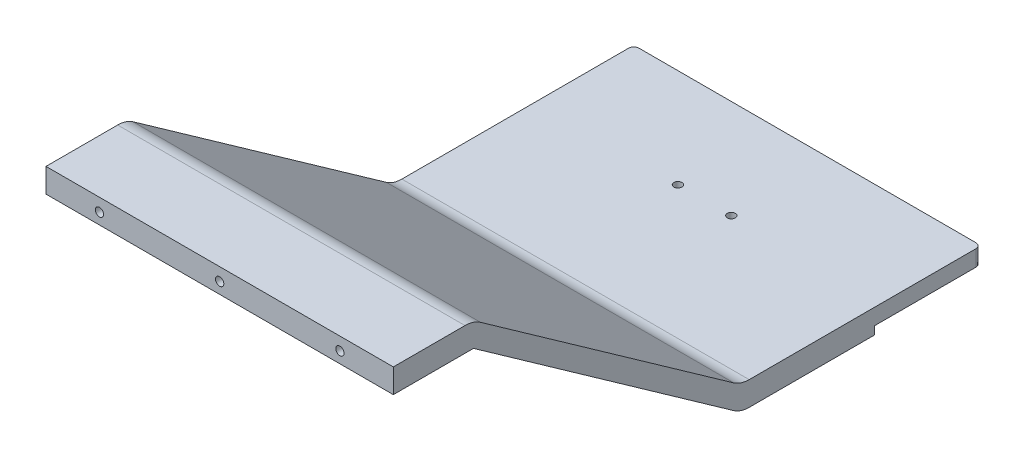
SolidWorks part; units mm, degrees
ref_plane "前视基准面" through (0, 0, 0) normal (0, 0, 1) x (1, 0, 0)
ref_plane "上视基准面" through (0, 0, 0) normal (0, 1, 0) x (1, 0, 0)
ref_plane "右视基准面" through (0, 0, 0) normal (1, 0, 0) x (0, 0, -1)
other "Configuration Table"
sketch "草图1" plane through (0, 0, 0) normal (0, 0, 1) x (1, 0, 0)
  line L0 (0, 0) -> (0, 79)
  line L1 (0, 79) -> (79, 79)
  line L2 (79, 79) -> (79, 70)
  line L3 (79, 70) -> (9, 70)
  line L4 (9, 70) -> (9, 0)
  line L5 (9, 0) -> (0, 0)
  dimension "D1" = 9
  dimension "D2" = 9
  dimension "D3" = 70
  dimension "D4" = 70
ref_plane "基准面1" through (0, 0, 100) normal (0, 0, 1) x (1, 0, 0)
sketch "草图2" plane through (0, 0, 100) normal (0, 0, 1) x (1, 0, 0)
  line L0 (0, 79) -> (-70.7107, 149.7107) construction
  line L1 (0, 0) -> (0, 79) construction
  line L2 (-70.7107, 149.7107) -> (-70.7107, 0)
  line L3 (-70.7107, 0) -> (-61.7107, 0)
  line L4 (-61.7107, 0) -> (-61.7107, 140.7107)
  line L5 (-61.7107, 140.7107) -> (79, 140.7107)
  line L6 (79, 140.7107) -> (79, 149.7107)
  line L7 (79, 149.7107) -> (-70.7107, 149.7107)
  line L8 (0, 0) -> (0, 79) construction
  line L9 (0, 79) -> (79, 79) construction
  dimension "D1" = 135
  dimension "D2" = 9
  dimension "D3" = 100
  dimension "D4" = 79
loft "放样1" add profiles "草图1", "草图2"
sketch "草图4" plane through (0, 0, 0) normal (0, 0, -1) x (-1, 0, 0)
  line L7 (-9, 0) -> (0, 0)
  line L8 (0, 0) -> (0, 79)
  line L9 (0, 79) -> (-79, 79)
  line L10 (-79, 79) -> (-79, 70)
  line L11 (-79, 70) -> (-77.7656, 70)
  line L12 (-77.7656, 70) -> (-9, 70)
  line L13 (-9, 70) -> (-9, 0)
  line L14 (-9, 0) -> (0, 0)
  line L15 (0, 0) -> (0, 79)
  line L16 (0, 79) -> (-79, 79)
  line L17 (-79, 79) -> (-79, 70)
  line L18 (-79, 70) -> (-77.7656, 70)
  line L19 (-77.7656, 70) -> (-9, 70)
  line L20 (-9, 70) -> (-9, 0)
  dimension "D1" = 0
extrude "凸台-拉伸1" add sketch "草图4" along normal blind 50
sketch "草图9" plane through (0, 0, -50) normal (0, 0, -1) x (-1, 0, 0)
  line L0 (-9, 70) -> (-9, 0) construction
  line L1 (-9, 70) -> (-55, 70)
  line L2 (-9, 70) -> (-9, 30)
  line L3 (-15, 64) -> (-55, 64)
  line L4 (-55, 70) -> (-55, 64)
  line L6 (-15, 64) -> (-15, 30)
  line L7 (-15, 30) -> (-9, 30)
  dimension "D1" = 6
  dimension "D2" = 46
  dimension "D3" = 6
  dimension "D4" = 40
extrude "凸台-拉伸3" add sketch "草图9" against normal blind 6
fillet "圆角1" radius 10 7 edges
sketch "草图11" plane through (0, 0, -44) normal (0, 0, 1) x (1, 0, 0)
  circle A0 centre (12, 45) radius 1.55
  circle A1 centre (12, 65) radius 1.55
  circle A2 centre (30, 67) radius 1.55
  circle A3 centre (50, 67) radius 1.55
  dimension "D1" = 3.1
extrude "切除-拉伸1" cut sketch "草图11" against normal through all
sketch "草图12" plane through (0, 0, -50) normal (0, 0, -1) x (-1, 0, 0)
  line L0 (0, 19) -> (0, 0)
  line L1 (0, 0) -> (0, 69) construction
  line L2 (0, 0) -> (-6, 0)
  line L3 (-9, 0) -> (0, 0) construction
  line L5 (-6, 0) -> (-6, 19)
  line L6 (0, 19) -> (-6, 19)
  line L7 (-2.9289, 76.0711) -> (-93.7798, -14.7798) construction
  line L8 (0, 0) -> (0, 69) construction
  line L9 (-60, 79) -> (-60, 73)
  line L10 (-79, 73) -> (-60, 73)
  line L11 (-79, 79) -> (-79, 73)
  line L12 (-60, 79) -> (-79, 79)
  arc A0 (0, 69) -> (-10, 79) centre (-10, 69) ccw construction
  dimension "D1" = 19
  dimension "D2" = 6
  dimension "D3" = 45
extrude "凸台-拉伸4" add sketch "草图12" along normal blind 40
fillet "圆角2" radius 2 9 edges at (3, 0, -90) (3, 19, -90) (9, 30, -47) (15, 30, -47) (15, 64, -47) (55, 70, -47) (55, 64, -47) (79, 76, -90) (60, 76, -90)
sketch "草图13" plane through (79, 0, 0) normal (1, 0, 0) x (0, 0, -1)
  line L0 (90, 79) -> (88, 79) construction
  line L1 (90, 79) -> (90, 73) construction
  line L9 (50, 73) -> (88, 73)
  line L10 (88, 73) -> (88, 79)
  line L11 (88, 79) -> (3.1784, 79)
  line L12 (-2.5951, 80.835) -> (-100, 149.7107)
  line L13 (-100, 149.7107) -> (-100, 149.2162)
  line L14 (-100, 149.2162) -> (-100, 140.7107)
  line L15 (-100, 140.7107) -> (-2.5951, 71.835)
  line L16 (3.1784, 70) -> (50, 70)
  line L17 (50, 70) -> (50, 73)
  line L18 (50, 73) -> (90, 73)
  line L19 (90, 73) -> (90, 79)
  line L20 (90, 79) -> (3.1784, 79)
  line L21 (-2.5951, 80.835) -> (-100, 149.7107)
  line L22 (-100, 149.7107) -> (-100, 149.2162)
  line L23 (-100, 149.2162) -> (-100, 140.7107)
  line L24 (-100, 140.7107) -> (-2.5951, 71.835)
  line L25 (3.1784, 70) -> (50, 70)
  line L26 (50, 70) -> (50, 73)
  arc A2 (-2.5951, 80.835) -> (3.1784, 79) centre (3.1784, 89) ccw
  arc A3 (-2.5951, 71.835) -> (3.1784, 70) centre (3.1784, 80) ccw
  arc A4 (-2.5951, 80.835) -> (3.1784, 79) centre (3.1784, 89) ccw
  arc A5 (-2.5951, 71.835) -> (3.1784, 70) centre (3.1784, 80) ccw
  dimension "D1" = 0
extrude "凸台-拉伸5" add sketch "草图13" along normal blind 130 separate body
delete or keep bodies "实体-删除/保留 1" type delete bodies bodies 112
sketch "草图14" plane through (0, 0, 100) normal (0, 0, 1) x (1, 0, 0)
  line L4 (79, 149.7107) -> (79, 140.7107)
  line L5 (79, 140.7107) -> (209, 140.7107)
  line L6 (209, 140.7107) -> (209, 149.7107)
  line L7 (209, 149.7107) -> (79, 149.7107)
  line L8 (79, 149.7107) -> (79, 140.7107)
  line L9 (79, 140.7107) -> (209, 140.7107)
  line L10 (209, 140.7107) -> (209, 149.7107)
  line L11 (209, 149.7107) -> (79, 149.7107)
  dimension "D1" = 0
extrude "凸台-拉伸6" add sketch "草图14" along normal blind 30
sketch "草图15" plane through (0, 0, 130) normal (0, 0, 1) x (1, 0, 0)
  line L0 (79, 149.7107) -> (79, 140.7107) construction
  line L1 (79, 140.7107) -> (209, 140.7107) construction
  circle A0 centre (99, 144.8907) radius 1.55
  circle A1 centre (144, 144.8907) radius 1.55
  circle A2 centre (189, 144.8907) radius 1.55
  dimension "D1" = 3.1
  dimension "D2" = 20
  dimension "D3" = 4.18
  dimension "D5" = 45
  dimension "D4" = 3
extrude "切除-拉伸2" cut sketch "草图15" against normal blind 5
fillet "圆角3" radius 2 2 edges at (79, 76, -90) (209, 76, -90)
sketch "草图16" plane through (0, 73, 0) normal (0, -1, 0) x (1, 0, 0)
  line L1 (144, 130) -> (144, 82.7932) construction
  line L2 (79, 130) -> (209, 130) construction
  line L3 (209, -50) -> (79, -50) construction
  circle A1 centre (152.5, -53) radius 1.5
  circle A2 centre (132.5, -53) radius 1.5
  point P4 (0, 0)
  dimension "D1" = 3
  dimension "D2" = 3
  dimension "D3" = 8.5
  dimension "D4" = 20
extrude "切除-拉伸3" cut sketch "草图16" against normal through all
fillet "圆角4" radius 10 1 edges at (144, 149.7107, 100)
